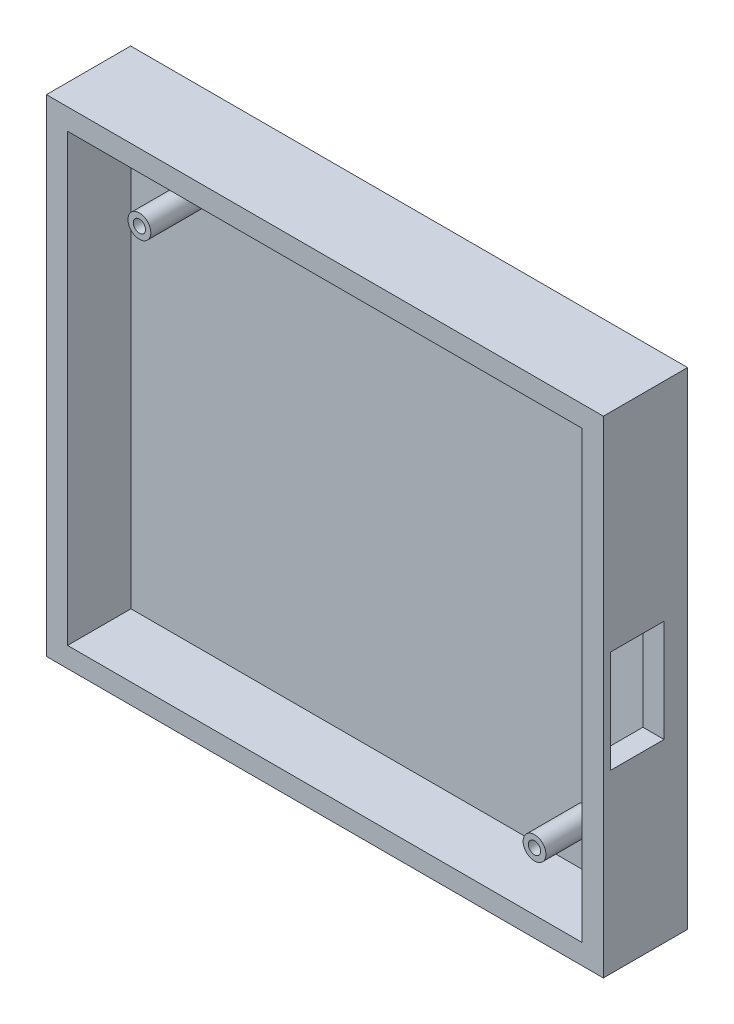
SolidWorks part; units mm, degrees
ref_plane "Front Plane" through (0, 0, 0) normal (0, 0, 1) x (1, 0, 0)
ref_plane "Top Plane" through (0, 0, 0) normal (0, 1, 0) x (1, 0, 0)
ref_plane "Right Plane" through (0, 0, 0) normal (1, 0, 0) x (0, 0, -1)
ref_plane "Plane1" through (0, 0, 1258.6525) normal (0, 0, -1) x (-1, 0, 0)
sketch "Sketch1" plane through (0, 0, 1258.6525) normal (0, 0, -1) x (-1, 0, 0)
  line L0 (-716.3719, 894.5808) -> (-592.685, 894.5808)
  line L1 (-716.3719, 894.5808) -> (-716.3719, 787.5564)
  line L2 (-592.685, 894.5808) -> (-592.685, 787.5564)
  line L3 (-716.3719, 787.5564) -> (-592.685, 787.5564)
  line L4 (-721.4519, 899.6608) -> (-587.605, 899.6608)
  line L5 (-587.605, 899.6608) -> (-587.605, 782.4764)
  line L6 (-721.4519, 782.4764) -> (-587.605, 782.4764)
  line L7 (-721.4519, 899.6608) -> (-721.4519, 782.4764)
  dimension "D1" = 5.08
extrude "Boss-Extrude2" add sketch "Sketch1" against normal blind 5 contours L1 L3 L2 L0
sketch "Sketch2" plane through (0, 0, 1258.6525) normal (0, 0, -1) x (-1, 0, 0)
  line L0 (-716.3719, 894.5808) -> (-592.685, 894.5808)
  line L1 (-716.3719, 894.5808) -> (-716.3719, 787.8009)
  line L2 (-592.685, 894.5808) -> (-592.685, 787.8009)
  line L3 (-716.3719, 787.8009) -> (-592.685, 787.8009)
  line L4 (-721.4519, 899.6608) -> (-587.605, 899.6608)
  line L5 (-587.605, 899.6608) -> (-587.605, 782.7209)
  line L6 (-721.4519, 782.7209) -> (-587.605, 782.7209)
  line L7 (-721.4519, 899.6608) -> (-721.4519, 782.7209)
  line M5 (-716.3719, 894.5808) -> (-716.3719, 787.5564)
  line M6 (-716.3719, 787.5564) -> (-592.685, 787.5564)
  line M7 (-592.685, 787.5564) -> (-592.685, 894.5808)
  line M8 (-592.685, 894.5808) -> (-716.3719, 894.5808)
  dimension "D1" = 5.08
extrude "Boss-Extrude4" add sketch "Sketch2" against normal blind 20.24 contours L4 L7 L6 L5 M5 M8 M7 M6
sketch "Sketch4" plane through (0, 0, 1263.6525) normal (0, 0, 1) x (1, 0, 0)
  circle A1 centre (607.328, 880.8409) radius 1.475
  circle A2 centre (702.2894, 798.9271) radius 1.475
  circle A3 centre (607.328, 880.8409) radius 2.745
  circle A4 centre (702.2894, 798.9271) radius 2.745
  dimension "D1" = 2.95
  dimension "D2" = 2.95
  dimension "D3" = 1.27
  dimension "D4" = 1.27
extrude "Boss-Extrude5" add sketch "Sketch4" along normal blind 12.62
sketch "Sketch5" plane through (721.4519, 0, 0) normal (1, 0, 0) x (0, 0, -1)
  line L0 (-1277.1377, 849.6995) -> (-1277.1377, 825.0753)
  line L1 (-1277.1377, 849.6995) -> (-1264.3012, 849.6995)
  line L2 (-1277.1377, 825.0753) -> (-1264.3012, 825.0753)
  line L3 (-1264.3012, 849.6995) -> (-1264.3012, 825.0753)
  point P0 (-1277.1377, 849.6995)
extrude "Cut-Extrude3" cut sketch "Sketch5" against normal blind 10
